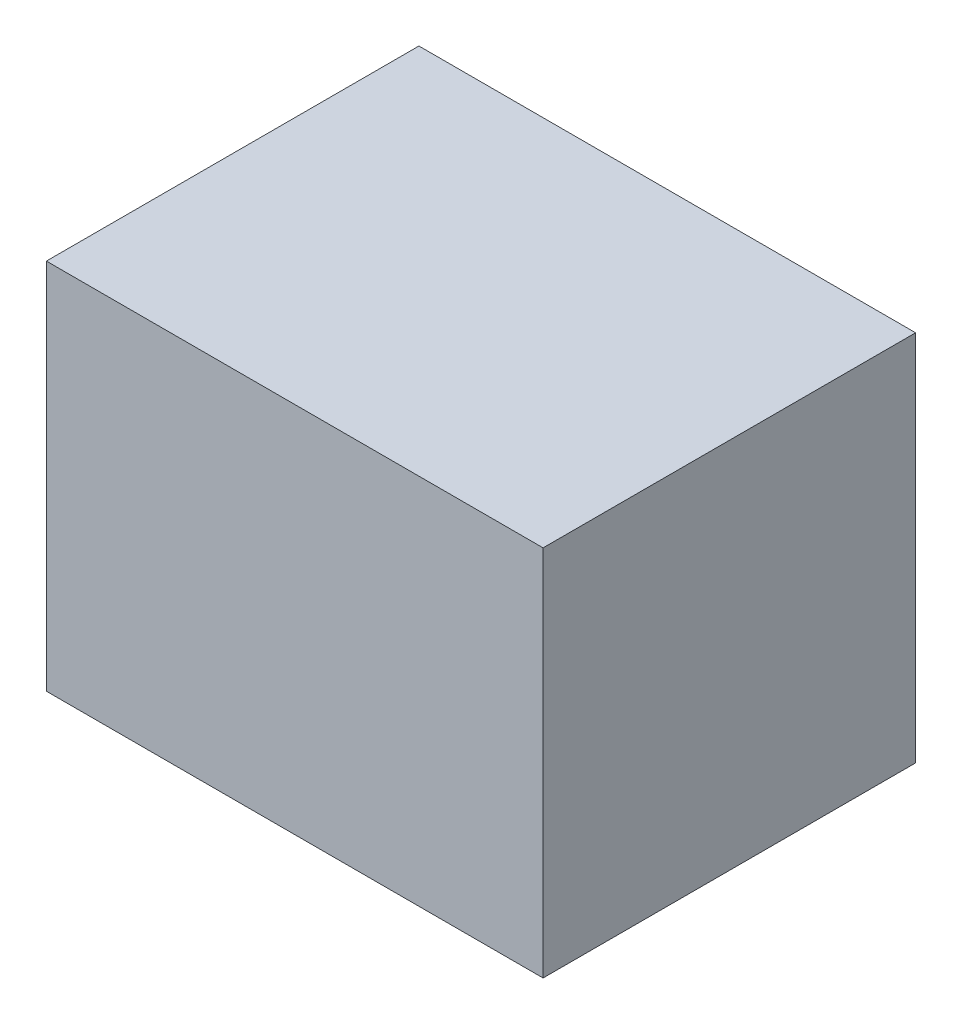
SolidWorks part; units mm, degrees
material "Gray Cast Iron"
ref_plane "Front Plane" through (0, 0, 0) normal (0, 0, 1) x (1, 0, 0)
ref_plane "Top Plane" through (0, 0, 0) normal (0, 1, 0) x (1, 0, 0)
ref_plane "Right Plane" through (0, 0, 0) normal (1, 0, 0) x (0, 0, -1)
sketch "Sketch1" plane through (0, 0, 0) normal (0, 0, 1) x (1, 0, 0)
  line L1 (0, 0) -> (400, 0)
  line L2 (0, 0) -> (0, 300)
  line L3 (0, 300) -> (400, 300)
  line L4 (400, 0) -> (400, 300)
  dimension "D1" = 400
  dimension "D2" = 300
extrude "Boss-Extrude1" add sketch "Sketch1" along normal blind 300
shell "Shell1" thickness 15
